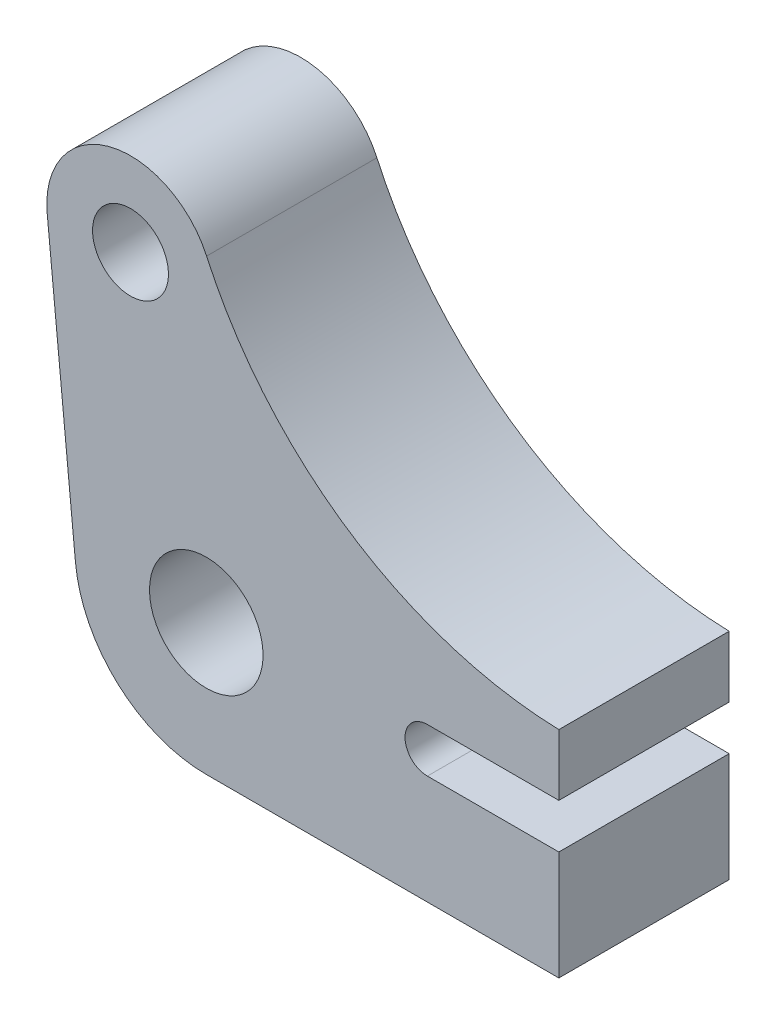
SolidWorks part; units mm, degrees
material "AISI 1020"
ref_plane "Plan de face" through (0, 0, 0) normal (0, 0, 1) x (1, 0, 0)
ref_plane "Plan de dessus" through (0, 0, 0) normal (0, 1, 0) x (1, 0, 0)
ref_plane "Plan de droite" through (0, 0, 0) normal (1, 0, 0) x (0, 0, -1)
sketch "Esquisse1" plane through (0, 0, 0) normal (0, 0, 1) x (1, 0, 0)
  line L0 (-74.2698, -14.0509) -> (-69.5495, -62.1624)
  line L4 (11.3454, -46.0143) -> (11.3454, -56.2773)
  line L5 (11.3454, -56.2773) -> (-10.6546, -56.2773)
  line L7 (-10.6546, -63.7512) -> (11.3454, -63.7512)
  line L8 (11.3454, -63.7512) -> (11.3454, -82.0143)
  line L9 (11.3454, -82.0143) -> (-47.6546, -82.0143)
  line L13 (-47.6546, -60.0143) -> (-47.6546, -14.6646) construction
  line L14 (-47.6546, -60.0143) -> (-60.3367, -12.6839) construction
  arc A0 (-69.5495, -62.1624) -> (-47.6546, -82.0143) centre (-47.6546, -60.0143) ccw
  arc A1 (-47.6012, -6.8696) -> (-74.2698, -14.0509) centre (-60.3367, -12.6839) ccw
  arc A3 (-10.6546, -63.7512) -> (-10.6546, -56.2773) centre (-10.6546, -60.0143) cw
  circle A4 centre (-60.3367, -12.6839) radius 6.35
  circle A5 centre (-47.6546, -60.0143) radius 9.5
  arc A6 (-47.6012, -6.8696) -> (11.3454, -46.0143) centre (13.3475, 20.9558) ccw
  point P3 (-28.2195, -4.1158)
  point P12 (4.6914, -34.1539)
  point P13 (-49.8697, -15.981)
  point P21 (-46.5757, -4.8629)
  point P22 (0, 0)
  point P23 (0, 0)
  point P24 (0, 0)
  point P25 (-44.274, -4.7123)
  point P26 (-42.9767, -8.5391)
  point P28 (13.3475, 20.9558)
  point P29 (0, 0)
  point P30 (0, 0)
  point P31 (0, 0)
  point P32 (0, 0)
  dimension "D1" = 22
  dimension "D2" = 14
  dimension "D3" = 67
  dimension "D4" = 36
  dimension "D6" = 59
  dimension "D7" = 22
  dimension "D8" = 49
  dimension "D9" = 0
  dimension "D11" = 0
  dimension "D5" = 0
  dimension "D12" = 15
  dimension "D13" = 22
  dimension "D14" = 0
extrude "Boss.-Extru.1" add sketch "Esquisse1" along normal blind 28.5
equation "\"A\"= 59"
equation "\"B\"= 22"
equation "\"C\"= 28.5"
equation "\"D6@Esquisse1\"=\"A\""
equation "\"D1@Esquisse1\"=\"B\""
equation "\"D13@Esquisse1\"=\"B\""
equation "\"D1@Boss.-Extru.1\"=\"C\""
